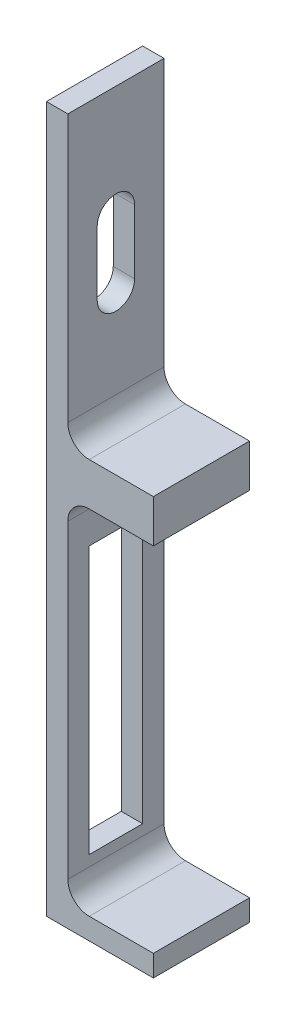
SolidWorks part; units mm, degrees
material "ПВХ Жесткий"
ref_plane "Спереди" through (0, 0, 0) normal (0, 0, 1) x (1, 0, 0)
ref_plane "Сверху" through (0, 0, 0) normal (0, 1, 0) x (1, 0, 0)
ref_plane "Справа" through (0, 0, 0) normal (1, 0, 0) x (0, 0, -1)
sketch "Эскиз1" plane through (0, 0, 0) normal (0, 0, 1) x (1, 0, 0)
  line L0 (0, 0) -> (10, 0)
  line L1 (10, 0) -> (10, 2)
  line L2 (10, 2) -> (2, 2)
  line L3 (2, 2) -> (2, 66)
  line L4 (2, 66) -> (0, 66)
  line L5 (0, 66) -> (0, 0)
  dimension "D1" = 2
  dimension "D2" = 66
  dimension "D3" = 10
extrude "Бобышка-Вытянуть1" add sketch "Эскиз1" along normal blind 9
sketch "Эскиз2" plane through (2, 0, 0) normal (1, 0, 0) x (0, 0, -1)
  line L0 (-4.5, 66) -> (-4.5, 2) construction
  line L1 (-9, 66) -> (0, 66) construction
  line L2 (-9, 2) -> (0, 2) construction
ref_plane "Плоскость1" through (0, 0, 4.5) normal (0, 0, 1) x (0, -1, 0)
sketch "Эскиз3" plane through (0, 0, 0) normal (-1, 0, 0) x (0, 0, 1)
  line L0 (9, 66) -> (0, 66) construction
  line L1 (4.5, 66) -> (4.5, 2) construction
  line L2 (4.5, 66) -> (4.5, 2) construction
  circle A1 centre (4.5, 52.52) radius 1.75
  dimension "D1" = 13.48
  dimension "D2" = 3.5
sketch "Эскиз4" plane through (0, 0, 0) normal (-1, 0, 0) x (0, 0, 1)
  line L0 (4.5, 55.52) -> (4.5, 49.52) construction
  line L1 (6.25, 55.52) -> (6.25, 49.52)
  line L2 (2.75, 55.52) -> (2.75, 49.52)
  line L3 (4.5, 66) -> (4.5, 43.3234) construction
  line L4 (9, 66) -> (0, 66) construction
  circle A0 centre (4.5, 52.52) radius 1.75 construction
  circle A1 centre (4.5, 52.52) radius 1.75 construction
  arc A2 (6.25, 55.52) -> (2.75, 55.52) centre (4.5, 55.52) ccw
  arc A3 (2.75, 49.52) -> (6.25, 49.52) centre (4.5, 49.52) ccw
  point P5 (4.5, 52.52)
  dimension "D1" = 6
extrude "Вырез-Вытянуть2" cut sketch "Эскиз4" against normal through all
sketch "Эскиз5" plane through (0, 0, 9) normal (0, 0, 1) x (1, 0, 0)
  line L0 (2, 2) -> (2, 66) construction
  line L1 (10, 2) -> (2, 2) construction
  line L2 (2, 2) -> (2, 9)
  line L3 (10, 2) -> (2, 2)
  line L4 (10, 2) -> (2, 9)
  dimension "D1" = 7
sketch "Эскиз6" plane through (2, 0, 0) normal (1, 0, 0) x (0, 0, -1)
  line L0 (-7, 5) -> (-2, 5)
  line L1 (-7, 5) -> (-7, 30)
  line L2 (-2, 5) -> (-2, 30)
  line L3 (-7, 30) -> (-2, 30)
  line L4 (-4.5, 30) -> (-4.5, 5) construction
  line L5 (-4.5, 66) -> (-4.5, 2) construction
  line L6 (-9, 2) -> (-9, 66) construction
  line L7 (-9, 2) -> (0, 2) construction
  dimension "D1" = 2
  dimension "D2" = 3
  dimension "D3" = 25
extrude "Вырез-Вытянуть3" cut sketch "Эскиз6" against normal through all
fillet "Скругление1" radius 2 1 edges at (2, 2, 4.5)
sketch "Эскиз7" plane through (0, 0, 9) normal (0, 0, 1) x (1, 0, 0)
  line L0 (2, 39) -> (2, 35)
  line L1 (2, 39) -> (10, 39)
  line L2 (2, 35) -> (10, 35)
  line L3 (10, 39) -> (10, 35)
  line L4 (2, 4) -> (2, 66) construction
  line L5 (0, 0) -> (10, 0) construction
  line L6 (10, 0) -> (10, 2) construction
  dimension "D1" = 35
  dimension "D2" = 4
extrude "Бобышка-Вытянуть2" add sketch "Эскиз7" against normal up to surface (9 mm away) up to face at (3.9408, 19.9408, 0)
fillet "Скругление2" radius 2 2 edges at (2, 39, 4.5) (2, 35, 4.5)
